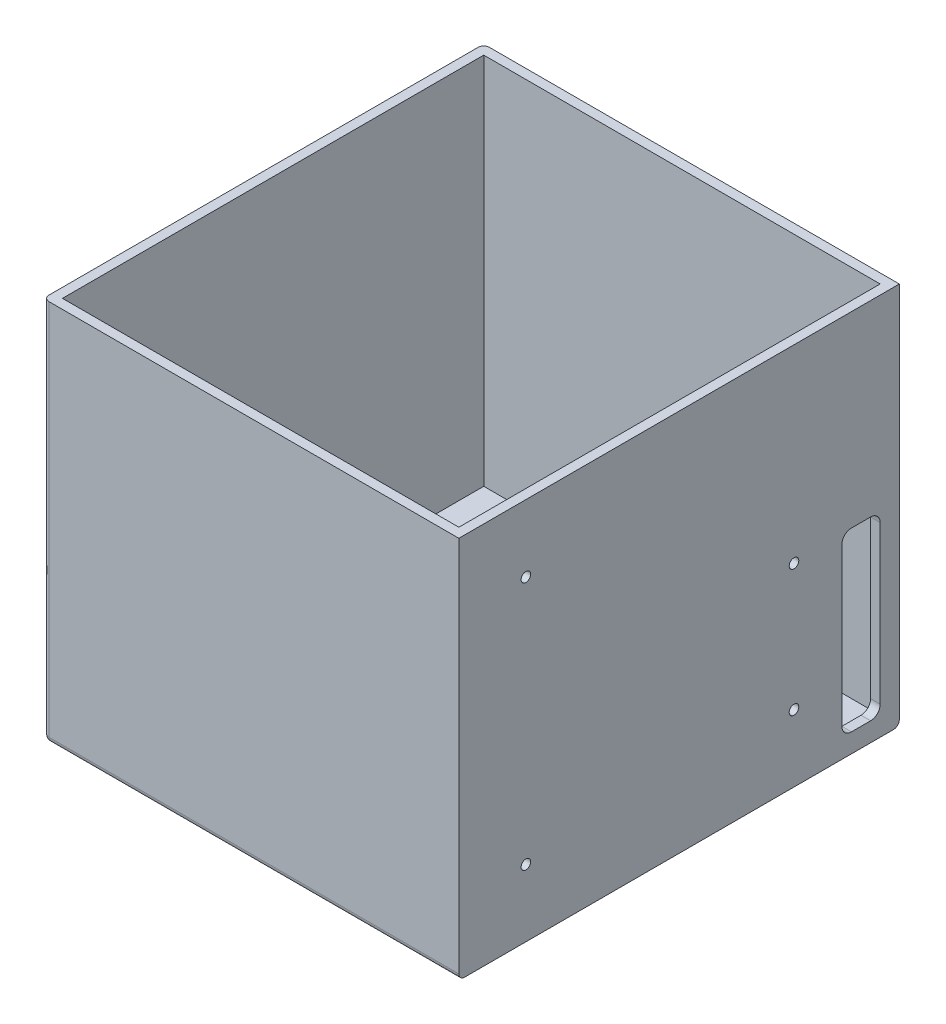
SolidWorks part; units mm, degrees
ref_plane "Front Plane" through (0, 0, 0) normal (0, 0, 1) x (1, 0, 0)
ref_plane "Top Plane" through (0, 0, 0) normal (0, 1, 0) x (1, 0, 0)
ref_plane "Right Plane" through (0, 0, 0) normal (1, 0, 0) x (0, 0, -1)
sketch "Sketch1" plane through (0, 0, 0) normal (0, 1, 0) x (1, 0, 0)
  line L1 (-99.7027, 89.7324) -> (117.2973, 89.7324)
  line L2 (-99.7027, 89.7324) -> (-99.7027, -140.2676)
  line L3 (-99.7027, -140.2676) -> (117.2973, -140.2676)
  line L4 (117.2973, 89.7324) -> (117.2973, -140.2676)
  line L5 (-99.7027, 89.7324) -> (117.2973, -140.2676) construction
  line L6 (-99.7027, -140.2676) -> (117.2973, 89.7324) construction
  point P4 (8.7973, -25.2676)
  dimension "D1" = 217
  dimension "D2" = 230
extrude "Boss-Extrude1" add sketch "Sketch1" along normal blind 200
sketch "Sketch2" plane through (0, 200, 0) normal (0, 1, 0) x (1, 0, 0)
  line L8 (-94.7027, 84.7324) -> (-94.7027, -135.2676)
  line L9 (-94.7027, -135.2676) -> (112.2973, -135.2676)
  line L10 (112.2973, -135.2676) -> (112.2973, 84.7324)
  line L11 (112.2973, 84.7324) -> (-94.7027, 84.7324)
  line L12 (-94.7027, 84.7324) -> (-94.7027, -135.2676)
  line L13 (-94.7027, -135.2676) -> (112.2973, -135.2676)
  line L14 (112.2973, -135.2676) -> (112.2973, 84.7324)
  line L15 (112.2973, 84.7324) -> (-94.7027, 84.7324)
  dimension "D1" = 5
extrude "Cut-Extrude1" cut sketch "Sketch2" against normal blind 195
fillet "Fillet1" radius 3 5 edges at (8.7973, 0, 140.2676) (8.7973, 0, -89.7324) (-99.7027, 0, 25.2676) (-99.7027, 100, 140.2676) (-99.7027, 100, -89.7324)
sketch "Sketch3" plane through (117.2973, 0, 0) normal (1, 0, 0) x (0, 0, -1)
  line L0 (-140.2676, 200) -> (-140.2676, 3) construction
  line L1 (-137.2676, 0) -> (86.7324, 0) construction
  line L5 (34.7324, 101.1848) -> (34.7324, 35)
  line L16 (34.7324, 101.1848) -> (-76.9483, 165)
  line L17 (-76.9483, 165) -> (-105.2676, 165)
  line L18 (-105.2676, 165) -> (-105.2676, 35)
  line L19 (-105.2676, 35) -> (34.7324, 35)
  circle A12 centre (-105.2676, 165) radius 2.5
  circle A13 centre (-105.2676, 35) radius 2.5
  circle A14 centre (34.7324, 101.1848) radius 2.5
  circle A15 centre (34.7324, 35) radius 2.5
  arc A25 (69.038, 94.82) -> (69.4093, 94.1506) centre (97.6416, 110.25) ccw
  dimension "D2" = 5
  dimension "D3" = 35
  dimension "D1" = 35
  dimension "D4" = 130
extrude "Cut-Extrude2" cut sketch "Sketch3" against normal blind 5 contours L17 A12 L18 | L18 A12 L17 | L19 A13 L18 | L19 A15 L5 | L5 A15 L19 | L5 A14 L16 | L16 A14 L5
sketch "Sketch4" plane through (117.2973, 0, 0) normal (1, 0, 0) x (0, 0, -1)
  line L0 (79.7324, 56.0502) -> (69.7324, 9.9668) construction
  line L3 (69.7324, 9.9668) -> (69.7324, 56.0502) construction
  line L4 (69.7324, 56.0502) -> (79.7324, 56.0502) construction
  line L5 (-140.2676, 200) -> (-140.2676, 3) construction
  line L6 (-137.2676, 0) -> (86.7324, 0) construction
  line L7 (89.7324, 200) -> (89.7324, 3) construction
  line L10 (83.0582, 12.128) -> (83.0582, 100.0387)
  line L11 (79.4133, 110.1729) -> (-68.9816, 194.9668)
  line L12 (-68.9816, 194.9668) -> (-128.2322, 194.9668)
  line L13 (-135.2676, 187.7577) -> (-135.2676, 12.161)
  line L14 (-128.2132, 5) -> (77.6045, 5)
  line L16 (64.7324, 102.1335) -> (74.7324, 102.1335)
  line L17 (59.7324, 97.1335) -> (59.7324, 14.9668)
  line L18 (64.7324, 9.9668) -> (74.7324, 9.9668)
  line L19 (79.7324, 97.1335) -> (79.7324, 14.9668)
  line L20 (59.7324, 102.1335) -> (79.7324, 9.9668) construction
  line L21 (59.7324, 9.9668) -> (79.7324, 102.1335) construction
  arc A0 (59.7324, 14.9668) -> (64.7324, 9.9668) centre (64.7324, 14.9668) ccw
  arc A1 (74.7324, 9.9668) -> (79.7324, 14.9668) centre (74.7324, 14.9668) ccw
  arc A2 (74.7324, 102.1335) -> (79.7324, 97.1335) centre (74.7324, 97.1335) cw
  arc A3 (64.7324, 102.1335) -> (59.7324, 97.1335) centre (64.7324, 97.1335) ccw
  arc A24 (83.0582, 100.0387) -> (80.7304, 102.9625) centre (80.0582, 100.0387) ccw
  arc A25 (80.6739, 106.3669) -> (80.7304, 102.9625) centre (82.5326, 104.695) ccw
  arc A26 (80.6739, 106.3669) -> (79.4133, 110.1729) centre (77.9249, 107.5682) ccw
  arc A27 (-128.2322, 194.9668) -> (-131.169, 192.5794) centre (-128.2322, 191.9668) ccw
  arc A28 (-133.0032, 190.6661) -> (-131.169, 192.5794) centre (-133.6163, 193.0898) ccw
  arc A29 (-133.0032, 190.6661) -> (-135.2676, 187.7577) centre (-132.2676, 187.7577) ccw
  arc A30 (-135.2676, 12.161) -> (-132.9905, 9.2494) centre (-132.2676, 12.161) ccw
  arc A31 (-131.1476, 7.343) -> (-132.9905, 9.2494) centre (-133.5929, 6.8231) ccw
  arc A32 (-131.1476, 7.343) -> (-128.2132, 5) centre (-128.2204, 8) ccw
  arc A33 (77.6045, 5) -> (80.5282, 7.3279) centre (77.6045, 8) ccw
  arc A34 (80.7304, 9.2042) -> (80.5282, 7.3279) centre (82.9311, 8.0181) ccw
  arc A35 (80.7304, 9.2042) -> (83.0582, 12.128) centre (80.0582, 12.128) ccw
  dimension "D2" = 5
  dimension "D1" = 5
  dimension "D3" = 5
  dimension "D4" = 10
extrude "Cut-Extrude3" cut sketch "Sketch4" against normal blind 10 contours L16 A3 L17 A0 L18 A1 L19 A2
